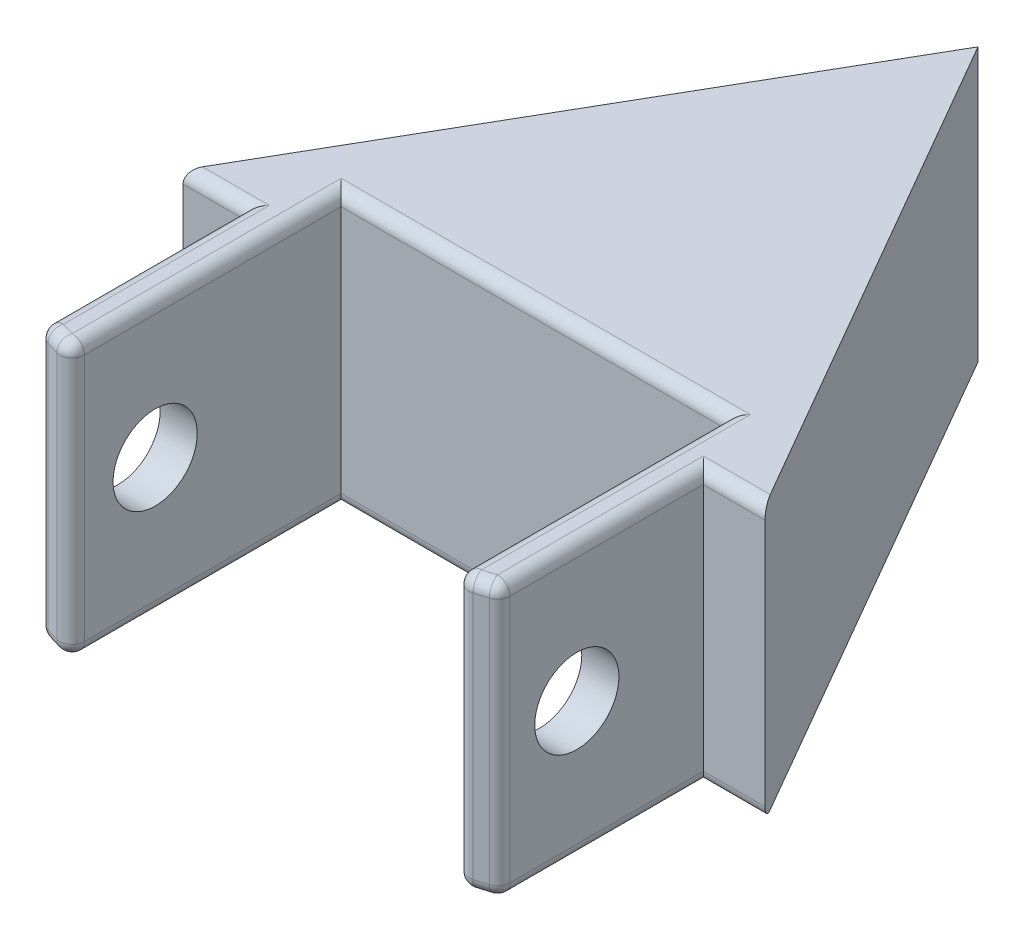
SolidWorks part; units mm, degrees
ref_plane "Front Plane" through (0, 0, 0) normal (0, 0, 1) x (1, 0, 0)
ref_plane "Top Plane" through (0, 0, 0) normal (0, 1, 0) x (1, 0, 0)
ref_plane "Right Plane" through (0, 0, 0) normal (1, 0, 0) x (0, 0, -1)
sketch "Sketch2" plane through (0, 0, 0) normal (0, 1, 0) x (1, 0, 0)
  line L0 (0, 0) -> (0, -76.2) construction
  line L1 (-38.1, -65.9911) -> (0, 0)
  line L2 (0, 0) -> (0, -76.2)
  arc A0 (0, -76.2) -> (-38.1, -65.9911) centre (0, 0) cw
  dimension "D1" = 76.2
extrude "Boss-Extrude1" add sketch "Sketch2" along normal blind 28
sketch "Sketch3" plane through (0, 0, 0) normal (0, 1, 0) x (1, 0, 0)
  line L0 (-38.1, -65.9911) -> (0, -76.2) construction
  line L7 (0, 0) -> (-19.05, -71.0956) construction
  line L8 (-19.05, -71.0956) -> (-19.722, -73.6035) construction
  line L10 (-19.722, -73.6035) -> (19.722, -73.6035) construction
  line L11 (19.722, -73.6035) -> (53.8815, -53.8815) construction
  line L12 (53.8815, -53.8815) -> (73.6035, -19.722) construction
  line L13 (73.6035, -19.722) -> (73.6035, 19.722) construction
  line L14 (73.6035, 19.722) -> (53.8815, 53.8815) construction
  line L15 (53.8815, 53.8815) -> (19.722, 73.6035) construction
  line L16 (19.722, 73.6035) -> (-19.722, 73.6035) construction
  line L17 (-19.722, 73.6035) -> (-53.8815, 53.8815) construction
  line L18 (-53.8815, 53.8815) -> (-73.6035, 19.722) construction
  line L19 (-73.6035, 19.722) -> (-73.6035, -19.722) construction
  line L20 (-73.6035, -19.722) -> (-53.8815, -53.8815) construction
  line L21 (-53.8815, -53.8815) -> (-19.722, -73.6035) construction
  circle A0 centre (0, 0) radius 76.2 construction
  circle A1 centre (0, 0) radius 76.2 construction
sketch "Sketch4" plane through (0, 28, 0) normal (0, 1, 0) x (1, 0, 0)
  line L2 (-19.722, -73.6035) -> (-19.722, -45.6036)
  line L3 (-19.722, -45.6036) -> (19.722, -45.6036)
  line L4 (19.722, -73.6035) -> (19.722, -45.6036)
  line L7 (-19.722, -73.6035) -> (-19.722, -89.0834)
  line L8 (-19.722, -89.0834) -> (19.722, -89.0834)
  line L9 (19.722, -73.6035) -> (19.722, -89.0834)
  dimension "D1" = 28
  dimension "D2" = 39.444
extrude "Cut-Extrude1" cut sketch "Sketch4" against normal through all both and the other way through all
sketch "Sketch5" plane through (-19.722, 0, 0) normal (1, 0, 0) x (0, 0, -1)
  line L0 (-73.6035, 28) -> (-45.6036, 0) construction
  line L1 (-45.6036, 28) -> (-73.6035, 0) construction
  line L3 (-59.6036, 14) -> (-64.6836, 14) construction
  circle A2 centre (-64.6836, 14) radius 6.35
  dimension "D2" = 12.7
  dimension "D1" = 5.08
extrude "Cut-Extrude2" cut sketch "Sketch5" against normal blind 4.572
sketch "Sketch6" plane through (-24.294, 0, 0) normal (1, 0, 0) x (0, 0, -1)
  line L0 (-68.3666, 14) -> (-68.4936, 14) construction
  line L1 (-71.0336, 14) -> (-70.7796, 14) construction
  line L2 (-64.6836, 17.81) -> (-64.6836, 20.096) construction
  line L3 (-64.6836, 14) -> (-45.6036, 14) construction
  line L4 (-45.6036, 0) -> (-45.6036, 28) construction
  line L5 (-64.6836, 14) -> (-61.7723, 18.0071) construction
  circle A0 centre (-64.6836, 14) radius 3.683
  circle A1 centre (-64.6836, 14) radius 3.81
  circle A2 centre (-64.6836, 14) radius 6.35 construction
  circle A3 centre (-64.6836, 14) radius 6.35 construction
  circle A4 centre (-64.6836, 14) radius 6.096
  circle A5 centre (-64.6836, 18.953) radius 1.143
  circle A6 centre (-61.7723, 18.0071) radius 1.143
  circle A7 centre (-59.973, 15.5306) radius 1.143
  circle A8 centre (-59.973, 12.4694) radius 1.143
  circle A9 centre (-61.7723, 9.9929) radius 1.143
  circle A10 centre (-64.6836, 9.047) radius 1.143
  circle A11 centre (-67.5949, 9.9929) radius 1.143
  circle A12 centre (-69.3941, 12.4694) radius 1.143
  circle A13 centre (-69.3941, 15.5306) radius 1.143
  circle A14 centre (-67.5949, 18.0071) radius 1.143
  point P38 (-64.6836, 14)
  dimension "D1" = 7.366
  dimension "D4" = 2.286
  dimension "D5" = 10
  dimension "D6" = 2.286
  dimension "D7" = 2.286
  dimension "D2" = 0.127
  dimension "D3" = 0.254
  dimension "D8" = 19.08
  dimension "D9" = 4.953
sketch "Sketch7" plane through (0, 0, 45.6036) normal (0, 0, 1) x (1, 0, 0)
  line L0 (-24.294, 14) -> (-21.5, 14) construction
  line L1 (-21.5, 14) -> (-19.722, 14) construction
  line L2 (-19.722, 0) -> (-19.722, 28) construction
  line L3 (-24.294, 14) -> (0, 14) construction
  line L4 (0, 28) -> (0, 0) construction
  dimension "D1" = 2.794
  dimension "D2" = 1.778
sketch "Sketch8" plane through (-19.722, 0, 0) normal (1, 0, 0) x (0, 0, -1)
  circle A0 centre (-64.6836, 14) radius 6.35
  circle A1 centre (-64.6836, 14) radius 4.318
  dimension "D1" = 8.636
extrude "Boss-Extrude4" add sketch "Sketch8" against normal blind 6.858
sketch "Sketch13" plane through (0, 0, 0) normal (0, 1, 0) x (1, 0, 0)
  line L0 (-19.722, -73.6035) -> (-19.722, -45.6036) construction
  line L2 (-23.532, -79.498) -> (-59.7536, -79.498)
  line L3 (-23.532, -79.498) -> (-23.532, -51.7)
  line L4 (-23.532, -51.7) -> (-59.7536, -51.7)
  line L5 (-59.7536, -79.498) -> (-59.7536, -51.7)
  line L6 (-23.532, -79.498) -> (-59.7536, -51.7) construction
  line L7 (-23.532, -51.7) -> (-59.7536, -79.498) construction
  point P0 (0, 0)
  point P5 (-41.6428, -65.599)
  dimension "D1" = 3.81
  dimension "D2" = 27.798
  dimension "D3" = 36.2216
extrude "Cut-Extrude6" cut sketch "Sketch13" against normal blind 2.54 and the other way through all
mirror "Mirror1" about plane through (0, 28, 0) normal (-1, 0, 0) of "Cut-Extrude1", "Cut-Extrude2", "Boss-Extrude4", "Cut-Extrude6", "Boss-Extrude1"
fillet "Fillet3" radius 1.27 22 edges at (21.6344, 28, 73.0643) (21.6344, 0, 73.0643) (26.6905, 0, 51.7) (0, 0, 45.6036) (23.532, 14, 72.4754) (23.532, 0, 62.0877) (23.532, 28, 62.0877) (26.6905, 28, 51.7) (-19.722, 0, 59.6036) (-19.722, 14, 73.6035) (-19.722, 28, 59.6036) (0, 28, 45.6036) (-21.6344, 0, 73.0643) (-26.6905, 0, 51.7) (-21.6344, 28, 73.0643) (-26.6905, 28, 51.7) (-23.532, 28, 62.0877) (-23.532, 0, 62.0877) (-23.532, 14, 72.4754) (19.722, 14, 73.6035) (19.722, 28, 59.6036) (19.722, 0, 59.6036)
sketch "Sketch10" plane through (0, 0, 0) normal (1, 0, 0) x (0, 0, -1)
  line L1 (0, 0) -> (-72.6366, 0)
  line L2 (0, 0) -> (0, 28)
  line L3 (0, 28) -> (-72.6366, 28)
  line L4 (-72.6366, 0) -> (-72.6366, 28)
  line L5 (0, 0) -> (-72.6366, 28) construction
  line L6 (0, 28) -> (-72.6366, 0) construction
  point P4 (-36.3183, 14)
